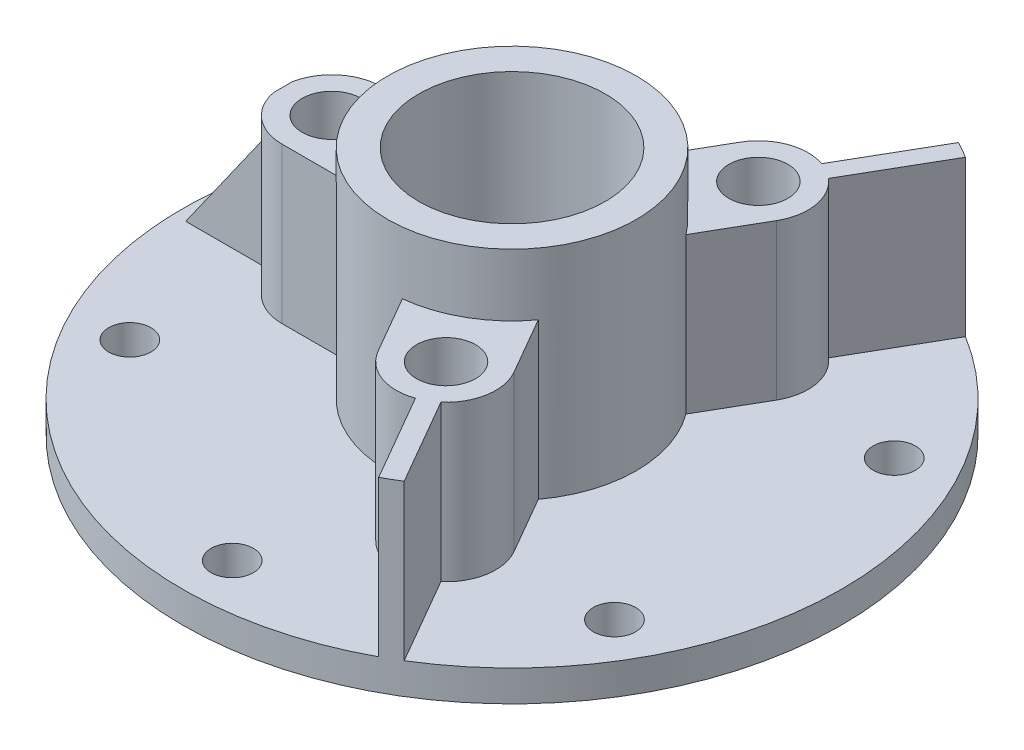
SolidWorks part; units mm, degrees
material "___"
ref_plane "Front Plane" through (0, 0, 0) normal (0, 0, 1) x (1, 0, 0)
ref_plane "Top Plane" through (0, 0, 0) normal (0, 1, 0) x (1, 0, 0)
ref_plane "Right Plane" through (0, 0, 0) normal (1, 0, 0) x (0, 0, -1)
sketch "Sketch1" plane through (0, 0, 0) normal (0, 1, 0) x (1, 0, 0)
  circle A0 centre (0, 0) radius 53
  dimension "D1" = 106
extrude "Boss-Extrude1" add sketch "Sketch1" along normal blind 5
sketch "Sketch2" plane through (0, 5, 0) normal (0, 1, 0) x (1, 0, 0)
  circle A0 centre (0, 0) radius 20
  dimension "D1" = 40
extrude "Boss-Extrude2" add sketch "Sketch2" along normal blind 35
sketch "Sketch3" plane through (0, 40, 0) normal (0, 1, 0) x (1, 0, 0)
  circle A0 centre (0, 0) radius 15
  dimension "D1" = 30
extrude "Cut-Extrude1" cut sketch "Sketch3" against normal through all
ref_plane "Plane1" through (0, 30, 0) normal (0, 1, 0) x (1, 0, 0)
sketch "Sketch4" plane through (0, 30, 0) normal (0, 1, 0) x (1, 0, 0)
  line L0 (53, 0) -> (-53, 0) construction
  line L1 (-29, 8) -> (-18.3303, 8)
  line L2 (-29, -8) -> (-18.3303, -8)
  line L3 (-36.8581, 1.5) -> (-52.9788, 1.5)
  line L4 (-36.8581, -1.5) -> (-52.9788, -1.5)
  circle A0 centre (0, 0) radius 53 construction
  circle A1 centre (0, 0) radius 20 construction
  circle A2 centre (0, 0) radius 29 construction
  arc A3 (-29, 8) -> (-36.8581, 1.5) centre (-29, 0) ccw
  arc A4 (-18.3303, 8) -> (-18.3303, -8) centre (0, 0) ccw
  circle A5 centre (-29, 0) radius 4.75
  arc A6 (-52.9788, 1.5) -> (-52.9788, -1.5) centre (0, 0) ccw
  arc A7 (-36.8581, -1.5) -> (-29, -8) centre (-29, 0) ccw
  point P8 (0, 0)
  dimension "D1" = 58
  dimension "D2" = 8
  dimension "D3" = 9.5
  dimension "D4" = 3
extrude "Boss-Extrude3" add sketch "Sketch4" against normal up to surface (25 mm away) up to face at (0, 5, 20)
sketch "Sketch5" plane through (0, 0, 1.5) normal (0, 0, 1) x (1, 0, 0)
  line L0 (-36.8581, 25) -> (-50.9788, 5)
  line L1 (-36.8581, 5) -> (-36.8581, 30) construction
  line L2 (53, 5) -> (-52.9788, 5) construction
  line L3 (-50.9788, 5) -> (-53.9788, 5)
  line L4 (-53.9788, 5) -> (-53.9788, 30)
  line L5 (-53.9788, 30) -> (-36.8581, 30)
  line L6 (-36.8581, 30) -> (-36.8581, 25)
  line L7 (-52.9788, 5) -> (-52.9788, 30) construction
  point P6 (0, 0)
  dimension "D1" = 3
  dimension "D2" = 5
  dimension "D3" = 2
extrude "Cut-Extrude2" cut sketch "Sketch5" against normal through all
pattern_circular "CirPattern1" count 3 over 360 about axis through (0, 0, 0) along (0, 1, 0) of "Boss-Extrude3"
sketch "Sketch6" plane through (0, 5, 0) normal (0, 1, 0) x (1, 0, 0)
  circle A0 centre (0, 0) radius 45 construction
  circle A1 centre (0, 45) radius 3.4
  circle A2 centre (0, 0) radius 45 construction
  circle A3 centre (38.9711, 22.5) radius 3.4
  circle A4 centre (0, 0) radius 45 construction
  circle A5 centre (38.9711, -22.5) radius 3.4
  circle A6 centre (0, 0) radius 45 construction
  circle A7 centre (0, -45) radius 3.4
  circle A8 centre (0, 0) radius 45 construction
  circle A9 centre (-38.9711, -22.5) radius 3.4
  circle A10 centre (0, 0) radius 45 construction
  circle A11 centre (-38.9711, 22.5) radius 3.4
  point P22 (0, 0)
  dimension "D1" = 90
  dimension "D2" = 6.8
  dimension "D3" = 6
extrude "Cut-Extrude3" cut sketch "Sketch6" against normal through all
